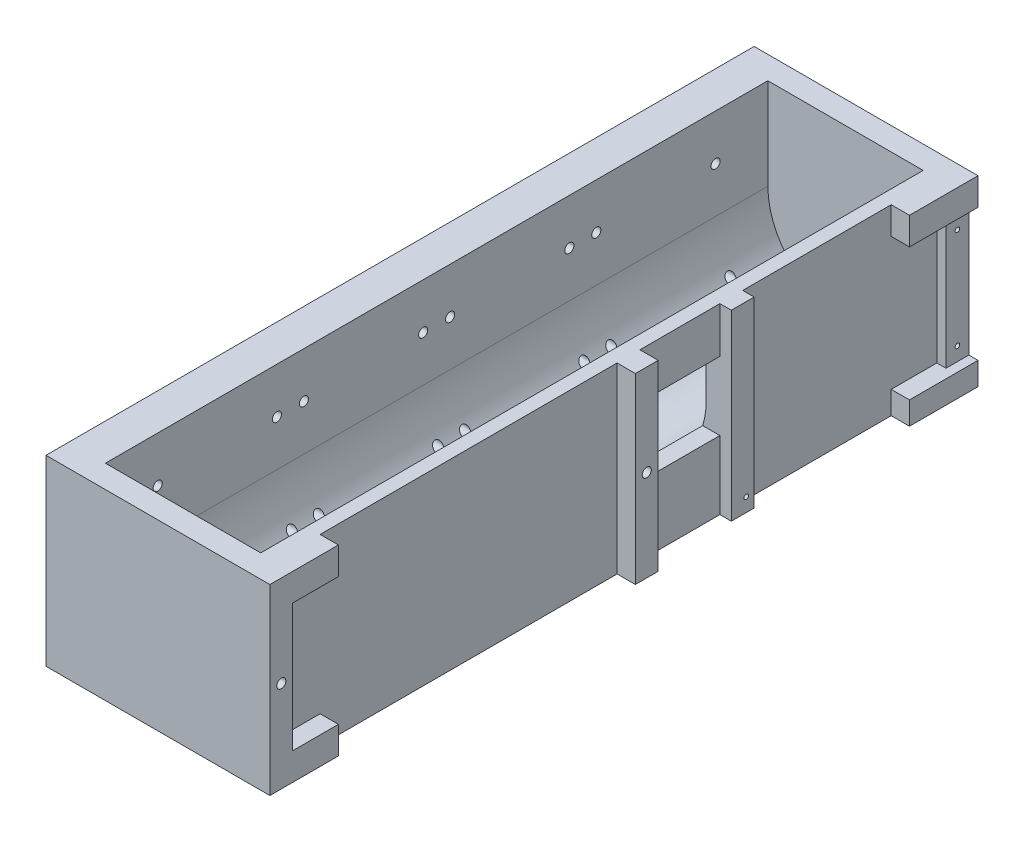
SolidWorks part; units mm, degrees
ref_plane "Front Plane" through (0, 0, 0) normal (0, 0, 1) x (1, 0, 0)
ref_plane "Top Plane" through (0, 0, 0) normal (0, 1, 0) x (1, 0, 0)
ref_plane "Right Plane" through (0, 0, 0) normal (1, 0, 0) x (0, 0, -1)
sketch "Sketch1" plane through (0, 0, 0) normal (0, 0, 1) x (1, 0, 0)
  line L1 (-15.7895, 18.5965) -> (24.2105, 18.5965)
  line L2 (-15.7895, 18.5965) -> (-15.7895, -21.4035)
  line L3 (-15.7895, -21.4035) -> (24.2105, -21.4035)
  line L4 (24.2105, 18.5965) -> (24.2105, -21.4035)
  dimension "D1" = 40
  dimension "D2" = 40
extrude "Boss-Extrude1" add sketch "Sketch1" along normal blind 155
sketch "Sketch2" plane through (0, 18.5965, 0) normal (0, 1, 0) x (1, 0, 0)
  line L0 (-15.7895, -155) -> (-15.7895, 0) construction
  line L1 (-12.7895, -5) -> (21.2105, -5)
  line L2 (-12.7895, -5) -> (-12.7895, -150)
  line L3 (-12.7895, -150) -> (21.2105, -150)
  line L4 (21.2105, -5) -> (21.2105, -150)
  line L5 (24.2105, 0) -> (-15.7895, 0) construction
  dimension "D1" = 34
  dimension "D2" = 3
  dimension "D3" = 145
  dimension "D4" = 5
extrude "Cut-Extrude1" cut sketch "Sketch2" against normal blind 20
sketch "Sketch3" plane through (0, 0, 5) normal (0, 0, 1) x (1, 0, 0)
  line L0 (21.2105, 18.5965) -> (-12.7895, 18.5965) construction
  line L1 (24.2105, -21.4035) -> (24.2105, 18.5965) construction
  circle A0 centre (4.2105, -1.4035) radius 17
  dimension "D1" = 20
  dimension "D2" = 20
extrude "Cut-Extrude2" cut sketch "Sketch3" along normal blind 145
sketch "Sketch4" plane through (-15.7895, 0, 0) normal (-1, 0, 0) x (0, 0, 1)
  line L1 (0, 18.5965) -> (155, 18.5965)
  line L2 (0, 18.5965) -> (0, -21.4035)
  line L3 (0, -21.4035) -> (155, -21.4035)
  line L4 (155, 18.5965) -> (155, -21.4035)
extrude "Boss-Extrude2" add sketch "Sketch4" along normal blind 5
sketch "Sketch5" plane through (-20.7895, 0, 0) normal (-1, 0, 0) x (0, 0, 1)
  line L0 (0, 18.5965) -> (0, -21.4035) construction
  line L1 (155, 18.5965) -> (0, 18.5965) construction
  circle A0 centre (16.45, 8.5965) radius 1
  circle A1 centre (42.55, 8.5965) radius 1
  circle A2 centre (48.45, 8.5965) radius 1
  circle A3 centre (74.55, 8.5965) radius 1
  circle A4 centre (80.45, 8.5965) radius 1
  circle A5 centre (106.55, 8.5965) radius 1
  circle A6 centre (112.45, 8.5965) radius 1
  circle A7 centre (138.55, 8.5965) radius 1
  point P20 (0, 0)
  point P21 (0, 0)
  circle B0 centre (16.45, -11.4535) radius 1
  circle B1 centre (42.55, -11.4535) radius 1
  circle B2 centre (48.45, -11.4535) radius 1
  circle B3 centre (74.55, -11.4535) radius 1
  circle B4 centre (80.45, -11.4535) radius 1
  circle B5 centre (106.55, -11.4535) radius 1
  circle B6 centre (112.45, -11.4535) radius 1
  circle B7 centre (138.55, -11.4535) radius 1
  dimension "D1" = 16.45
  dimension "D3" = 42.55
  dimension "D5" = 48.45
  dimension "D7" = 74.55
  dimension "D9" = 80.45
  dimension "D10" = 106.55
  dimension "D11" = 112.45
  dimension "D12" = 138.55
  dimension "D2" = 10
  dimension "D4" = 10
  dimension "D6" = 10
  dimension "D8" = 10
  dimension "D13" = 16.45
  dimension "D14" = 30.05
sketch_block_instance "Block1-1"
sketch_block "Block1"
extrude "Cut-Extrude3" cut sketch "Sketch5" against normal blind 13
sketch "Sketch6" plane through (24.2105, 0, 0) normal (1, 0, 0) x (0, 0, -1)
  line L0 (-155, -21.4035) -> (0, -21.4035) construction
  line L1 (-155, 18.5965) -> (-150, 18.5965)
  line L2 (-155, 18.5965) -> (-155, -21.4035)
  line L3 (-155, -21.4035) -> (-150, -21.4035)
  line L4 (-150, 18.5965) -> (-150, -21.4035)
  dimension "D1" = 5
extrude "Boss-Extrude3" add sketch "Sketch6" along normal blind 4
sketch "Sketch7" plane through (24.2105, 0, 0) normal (1, 0, 0) x (0, 0, -1)
  line L0 (-150, 18.5965) -> (0, 18.5965) construction
  line L1 (-75, 18.5965) -> (-70, 18.5965)
  line L2 (-75, 18.5965) -> (-75, -21.4035)
  line L3 (-75, -21.4035) -> (-70, -21.4035)
  line L4 (-70, 18.5965) -> (-70, -21.4035)
  line L5 (-150, -21.4035) -> (0, -21.4035) construction
  line L6 (-155, 18.5965) -> (-155, -21.4035) construction
  dimension "D1" = 5
  dimension "D2" = 80
extrude "Boss-Extrude4" add sketch "Sketch7" along normal blind 4
sketch "Sketch8" plane through (24.2105, 0, 0) normal (1, 0, 0) x (0, 0, -1)
  line L0 (-70, -21.4035) -> (0, -21.4035) construction
  line L1 (0, 18.5965) -> (-5, 18.5965)
  line L2 (0, 18.5965) -> (0, -21.4035)
  line L3 (0, -21.4035) -> (-5, -21.4035)
  line L4 (-5, 18.5965) -> (-5, -21.4035)
  dimension "D1" = 5
extrude "Boss-Extrude5" add sketch "Sketch8" along normal blind 2
sketch "Sketch9" plane through (24.2105, 0, 0) normal (1, 0, 0) x (0, 0, -1)
  line L0 (-70, 18.5965) -> (-5, 18.5965) construction
  line L1 (-52.5, 18.5965) -> (-47.5, 18.5965)
  line L2 (-52.5, 18.5965) -> (-52.5, -21.4035)
  line L3 (-52.5, -21.4035) -> (-47.5, -21.4035)
  line L4 (-47.5, 18.5965) -> (-47.5, -21.4035)
  line L5 (-70, -21.4035) -> (-5, -21.4035) construction
  line L6 (0, -21.4035) -> (0, 18.5965) construction
  dimension "D1" = 5
  dimension "D2" = 52.5
extrude "Boss-Extrude7" add sketch "Sketch9" along normal blind 2.5
sketch "Sketch12" plane through (26.2105, 0, 0) normal (1, 0, 0) x (0, 0, -1)
  line L0 (0, -21.4035) -> (0, 18.5965) construction
  line L1 (0, 18.5965) -> (-5, 18.5965) construction
  circle A0 centre (-2.5, 8.5965) radius 0.5
  circle A1 centre (-2.5, -13.4035) radius 0.5
  dimension "D1" = 2.5
  dimension "D3" = 22
  dimension "D2" = 10
extrude "Cut-Extrude5" cut sketch "Sketch12" against normal blind 10
sketch "Sketch13" plane through (26.7105, 0, 0) normal (1, 0, 0) x (0, 0, -1)
  line L0 (-47.5, 18.5965) -> (-52.5, 18.5965) construction
  circle A0 centre (-49.2333, -18.4035) radius 0.5
  circle A1 centre (-2.5, -13.4035) radius 0.5 construction
  dimension "D1" = 37
  dimension "D2" = 47
extrude "Cut-Extrude6" cut sketch "Sketch13" against normal blind 10
sketch "Sketch14" plane through (28.2105, 0, 0) normal (1, 0, 0) x (0, 0, -1)
  line L0 (-75, 18.5965) -> (-75, -21.4035) construction
  line L1 (-70, 18.5965) -> (-75, 18.5965) construction
  circle A0 centre (-72.5, -1.4035) radius 1
  dimension "D1" = 2.5
  dimension "D2" = 20
extrude "Cut-Extrude7" cut sketch "Sketch14" against normal blind 10
sketch "Sketch15" plane through (28.2105, 0, 0) normal (1, 0, 0) x (0, 0, -1)
  line L0 (-150, 18.5965) -> (-155, 18.5965) construction
  line L1 (-155, 18.5965) -> (-155, -21.4035) construction
  circle A0 centre (-152.5, -1.4035) radius 1
  dimension "D1" = 20
  dimension "D2" = 2.5
extrude "Cut-Extrude8" cut sketch "Sketch15" against normal blind 10
sketch "Sketch16" plane through (24.2105, 0, 0) normal (1, 0, 0) x (0, 0, -1)
  line L0 (-70, -21.4035) -> (-70, 18.5965) construction
  line L1 (-70, 8.5965) -> (-52.5, 8.5965)
  line L2 (-70, 8.5965) -> (-70, -6.4035)
  line L3 (-70, -6.4035) -> (-52.5, -6.4035)
  line L4 (-52.5, 8.5965) -> (-52.5, -6.4035)
  line L5 (-52.5, 18.5965) -> (-52.5, -21.4035) construction
  line L6 (-70, 18.5965) -> (-52.5, 18.5965) construction
  dimension "D1" = 15
  dimension "D2" = 10
extrude "Cut-Extrude9" cut sketch "Sketch16" against normal blind 10
sketch "Sketch17" plane through (-20.7895, 0, 0) normal (-1, 0, 0) x (0, 0, 1)
  line L0 (0, 18.5965) -> (0, -21.4035) construction
  line L1 (13.5, 13.5965) -> (141.5, 13.5965)
  line L2 (13.5, 13.5965) -> (13.5, 11.5965)
  line L3 (13.5, 11.5965) -> (141.5, 11.5965)
  line L4 (141.5, 13.5965) -> (141.5, 11.5965)
  circle A0 centre (16.45, 8.5965) radius 1 construction
  point P6 (0, 0)
  dimension "D3" = 3
  dimension "D1" = 128
  dimension "D2" = 2
  dimension "D4" = 13.5
extrude "Boss-Extrude8" add sketch "Sketch17" along normal blind 2
sketch "Sketch18" plane through (-22.7895, 0, 0) normal (-1, 0, 0) x (0, 0, 1)
  line L0 (0, 18.5965) -> (0, -21.4035) construction
  line L1 (13.5, -14.4535) -> (141.5, -14.4535)
  line L2 (13.5, -14.4535) -> (13.5, -16.4535)
  line L3 (13.5, -16.4535) -> (141.5, -16.4535)
  line L4 (141.5, -14.4535) -> (141.5, -16.4535)
  circle A0 centre (16.45, -11.4535) radius 1 construction
  point P6 (0, 0)
  point P9 (0, 0)
  dimension "D3" = 3
  dimension "D1" = 128
  dimension "D2" = 2
  dimension "D4" = 13.5
extrude "Boss-Extrude9" add sketch "Sketch18" along normal blind 2 separate body
sketch "Sketch21" plane through (24.2105, 0, 0) normal (1, 0, 0) x (0, 0, -1)
  line L1 (-150, 18.5965) -> (-140, 18.5965)
  line L2 (-150, 18.5965) -> (-150, 12.5965)
  line L3 (-150, 12.5965) -> (-140, 12.5965)
  line L4 (-140, 18.5965) -> (-140, 12.5965)
  dimension "D1" = 6
  dimension "D2" = 10
extrude "Boss-Extrude10" add sketch "Sketch21" along normal blind 4
sketch "Sketch22" plane through (24.2105, 0, 0) normal (1, 0, 0) x (0, 0, -1)
  line L1 (-140, -15.4035) -> (-150, -15.4035)
  line L2 (-140, -15.4035) -> (-140, -21.4035)
  line L3 (-140, -21.4035) -> (-150, -21.4035)
  line L4 (-150, -15.4035) -> (-150, -21.4035)
  dimension "D1" = 10
  dimension "D2" = 6
extrude "Boss-Extrude11" add sketch "Sketch22" along normal blind 4
sketch "Sketch23" plane through (24.2105, 0, 0) normal (1, 0, 0) x (0, 0, -1)
  line L1 (-5, 18.5965) -> (-15, 18.5965)
  line L2 (-5, 18.5965) -> (-5, 12.5965)
  line L3 (-5, 12.5965) -> (-15, 12.5965)
  line L4 (-15, 18.5965) -> (-15, 12.5965)
  dimension "D1" = 10
  dimension "D2" = 6
extrude "Boss-Extrude12" add sketch "Sketch23" along normal blind 4
sketch "Sketch24" plane through (0, 0, 5) normal (0, 0, -1) x (-1, 0, 0)
  line L1 (-28.2105, 18.5965) -> (-26.2105, 18.5965)
  line L2 (-28.2105, 18.5965) -> (-28.2105, 12.5965)
  line L3 (-28.2105, 12.5965) -> (-26.2105, 12.5965)
  line L4 (-26.2105, 18.5965) -> (-26.2105, 12.5965)
extrude "Boss-Extrude13" add sketch "Sketch24" along normal blind 5
sketch "Sketch25" plane through (24.2105, 0, 0) normal (1, 0, 0) x (0, 0, -1)
  line L1 (-5, -21.4035) -> (-15, -21.4035)
  line L2 (-5, -21.4035) -> (-5, -16.4035)
  line L3 (-5, -16.4035) -> (-15, -16.4035)
  line L4 (-15, -21.4035) -> (-15, -16.4035)
  dimension "D1" = 5
  dimension "D2" = 10
extrude "Boss-Extrude16" add sketch "Sketch25" along normal blind 4
sketch "Sketch27" plane through (0, 0, 5) normal (0, 0, -1) x (-1, 0, 0)
  line L1 (-28.2105, -16.4035) -> (-26.2105, -16.4035)
  line L2 (-28.2105, -16.4035) -> (-28.2105, -21.4035)
  line L3 (-28.2105, -21.4035) -> (-26.2105, -21.4035)
  line L4 (-26.2105, -16.4035) -> (-26.2105, -21.4035)
extrude "Boss-Extrude17" add sketch "Sketch27" along normal blind 5
